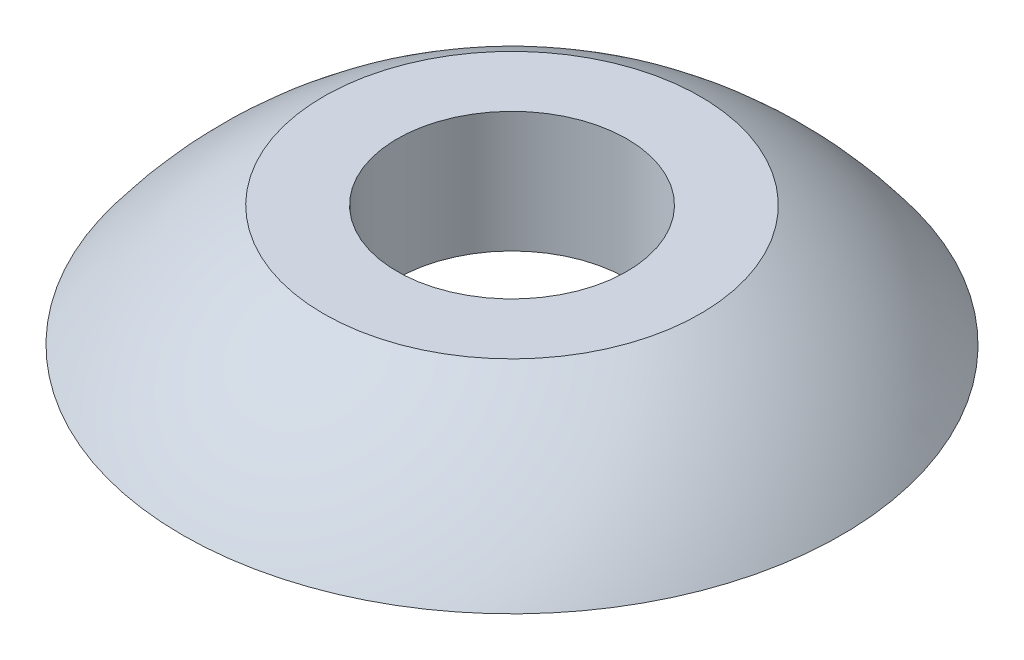
SolidWorks part; units mm, degrees
ref_plane "Front Plane" through (0, 0, 0) normal (0, 0, 1) x (1, 0, 0)
ref_plane "Top Plane" through (0, 0, 0) normal (0, 1, 0) x (1, 0, 0)
ref_plane "Right Plane" through (0, 0, 0) normal (1, 0, 0) x (0, 0, -1)
sketch "Sketch2" plane through (0, 0, 0) normal (1, 0, 0) x (0, 0, -1)
  line L0 (-33.8, 0) -> (0, 0)
  line L1 (0, 0) -> (0, 33.8) construction
  line L2 (-27.2478, 20) -> (0, 20)
  line L3 (-15.5705, 30) -> (0, 30)
  line L4 (-9.5, 30) -> (-9.5, 20)
  line L5 (-11.5, 20) -> (-11.5, 28)
  line L6 (-11.5, 28) -> (-15.0745, 28)
  arc A0 (-33.8, 0) -> (0, 33.8) centre (0, 0) cw
  arc A1 (-31.8, 0) -> (0, 31.8) centre (0, 0) cw
  dimension "D1" = 67.6
  dimension "D2" = 10
  dimension "D3" = 20
  dimension "D4" = 19
  dimension "D6" = 2
  dimension "D7" = 2
  dimension "D5" = 2
revolve "Revolve1" add sketch "Sketch2" angle 360 about L1
sketch "Sketch3" plane through (0, 20, 0) normal (0, -1, 0) x (1, 0, 0)
  line L0 (0, 23.1143) -> (0, 0)
  line L1 (0, 0) -> (16.5136, 16.1733)
  line L2 (23.1143, 0) -> (0, 0)
  line L3 (0, -23.1143) -> (0, 0)
  line L4 (0, 0) -> (-16.5128, -16.174)
  line L5 (-23.1143, 0) -> (0, 0)
  line L6 (-16.5128, 16.174) -> (0, 0.2323)
  line L7 (0, 0) -> (15.2603, -17.3608)
  circle A0 centre (0, 0) radius 26.75
  circle A1 centre (0, 0) radius 23.1143
  circle A2 centre (0, 0) radius 7.397
  circle M1 centre (0, 0) radius 24.7233
  dimension "D1" = 53.5
extrude "Boss-Extrude1" [suppressed] add sketch "Sketch3" along normal blind 23 separate body contours A0 M1 | A1 M1 | A2 L0 A1 L6 | A2 L2 A1 L1 | A2 L5 A1 L4 | A2 L3 A1 L7
